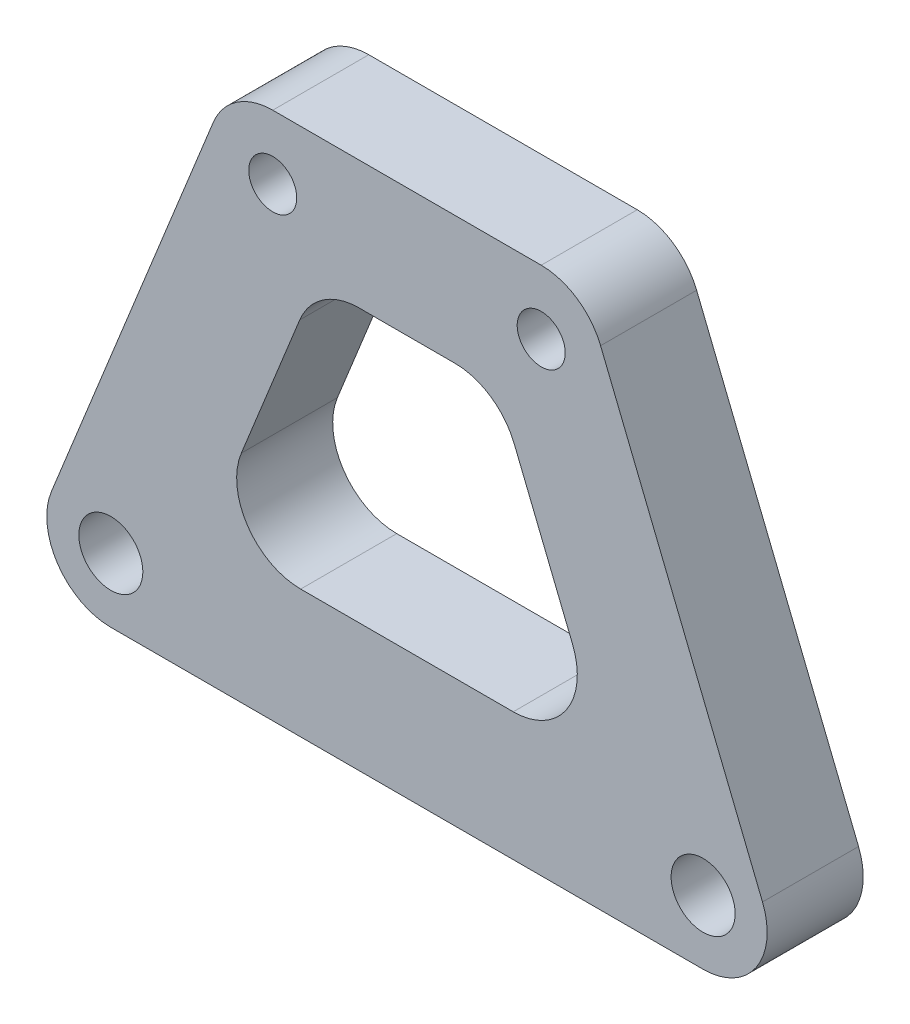
SolidWorks part; units mm, degrees
material "Vero PureWhite"
ref_plane "前视基准面" through (0, 0, 0) normal (0, 0, 1) x (1, 0, 0)
ref_plane "上视基准面" through (0, 0, 0) normal (0, 1, 0) x (1, 0, 0)
ref_plane "右视基准面" through (0, 0, 0) normal (1, 0, 0) x (0, 0, -1)
other "Configuration Table"
sketch "d" plane through (0, 0, 0) normal (0, 0, 1) x (1, 0, 0)
  line L0 (0, 0) -> (37, 0) construction
  line L1 (0, 0) -> (10.1144, 25.034)
  line L2 (10.1144, 25.034) -> (26.8856, 25.034)
  line L3 (26.8856, 25.034) -> (37, 0)
  line L5 (0, 0) -> (37, 0)
  line L6 (-5.9302, -4) -> (7.4163, 29.034)
  line L7 (7.4163, 29.034) -> (29.5837, 29.034)
  line L8 (29.5837, 29.034) -> (42.9302, -4)
  line L9 (-5.9302, -4) -> (42.9302, -4)
  line L10 (5.9302, 4) -> (12.8124, 21.034)
  line L11 (12.8124, 21.034) -> (24.1876, 21.034)
  line L12 (24.1876, 21.034) -> (31.0698, 4)
  line L13 (5.9302, 4) -> (31.0698, 4)
  dimension "D1" = 37
  dimension "D2" = 27
  dimension "D3" = 27
  dimension "D4" = 68
  dimension "D5" = 4
  dimension "D6" = 4
extrude "凸台-拉伸1" add sketch "d" along normal blind 6 contours L6 L9 L8 L7 L5 L1 L2 L3 | L1 L5 L3 L2 L13 L10 L11 L12
sketch "草图5" plane through (0, 0, 6) normal (0, 0, 1) x (1, 0, 0)
  circle A0 centre (0, 0) radius 2
  circle A1 centre (37, 0) radius 2
  circle A2 centre (26.8856, 25.034) radius 1.5
  circle A3 centre (10.1144, 25.034) radius 1.5
  dimension "D4" = 4
  dimension "D5" = 4
  dimension "D6" = 3
  dimension "D7" = 3
extrude "切除-拉伸3" cut sketch "草图5" against normal through all
fillet "圆角1" radius 4 8 edges at (-5.9302, -4, 3) (42.9302, -4, 3) (29.5837, 29.034, 3) (7.4163, 29.034, 3) (5.9302, 4, 3) (31.0698, 4, 3) (24.1876, 21.034, 3) (12.8124, 21.034, 3)
